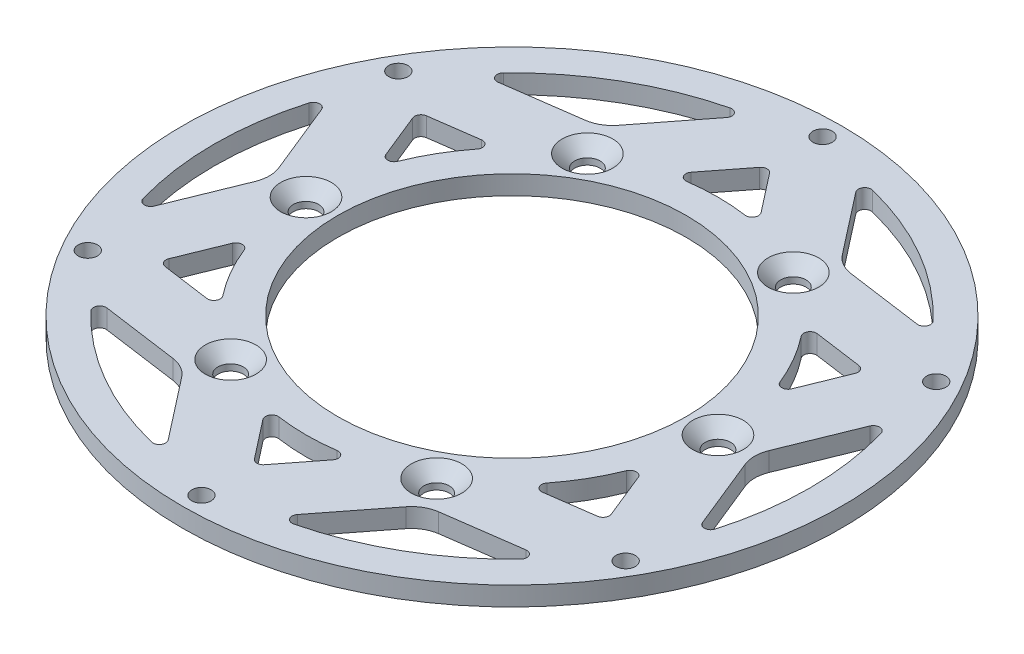
SolidWorks part; units mm, degrees
material "Thornel Mat VMA"
ref_plane "前视基准面" through (0, 0, 0) normal (0, 0, 1) x (1, 0, 0)
ref_plane "上视基准面" through (0, 0, 0) normal (0, 1, 0) x (1, 0, 0)
ref_plane "右视基准面" through (0, 0, 0) normal (1, 0, 0) x (0, 0, -1)
sketch "草图1" plane through (0, 0, 0) normal (0, 1, 0) x (1, 0, 0)
  circle A0 centre (0, 0) radius 52
  circle A1 centre (0, 0) radius 49 construction
  circle A2 centre (0, 0) radius 32.5 construction
  circle A3 centre (0, 49) radius 1.525
  circle A4 centre (-16.25, 28.1458) radius 2
  circle A5 centre (42.4352, 24.5) radius 1.525
  circle A6 centre (16.25, 28.1458) radius 2
  circle A7 centre (42.4352, -24.5) radius 1.525
  circle A8 centre (32.5, 0) radius 2
  circle A9 centre (0, -49) radius 1.525
  circle A10 centre (16.25, -28.1458) radius 2
  circle A11 centre (-42.4352, -24.5) radius 1.525
  circle A12 centre (-16.25, -28.1458) radius 2
  circle A13 centre (-42.4352, 24.5) radius 1.525
  circle A14 centre (-32.5, 0) radius 2
  circle A15 centre (0, 0) radius 27.5
  dimension "D1" = 104
  dimension "D2" = 65
  dimension "D3" = 3
  dimension "D4" = 3.05
  dimension "D5" = 4
  dimension "D7" = 55
  dimension "D6" = 6
extrude "凸台-拉伸1" add sketch "草图1" along normal blind 3
hole_wizard "孔1" positions "草图2" profile "草图3" legacy end condition through all
sketch "草图2" plane through (0, 3, 0) normal (0, 1, 0) x (1, 0, 0)
  point P0 (-16.25, 28.1458)
  point P7 (16.25, 28.1458)
  point P8 (32.5, 0)
  point P9 (16.25, -28.1458)
  point P10 (-16.25, -28.1458)
  point P11 (-32.5, 0)
  dimension "D1" = 6
sketch "草图3" plane through (-16.25, 3, -28.1458) normal (1, 0, 0) x (0, 0, 1)
  line L0 (0, 0) -> (0, 3)
  line L1 (0, 3) -> (2, 3)
  line L2 (2, 3) -> (2, 2)
  line L3 (2, 2) -> (4, 0)
  line L4 (4, 0) -> (0, 0)
  line L5 (0, -6.4453) -> (0, 115.525) construction
  line L6 (-2, 2) -> (-4, 0) construction
  dimension "直径" = 4
  dimension "深度" = 3
  dimension "锥坑角度" = 90
  dimension "锥坑直径" = 8
sketch "草图5" plane through (0, 3, 0) normal (0, 1, 0) x (1, 0, 0)
  line L0 (0, 49) -> (-16.25, 28.1458) construction
  line L1 (-16.25, 28.1458) -> (-42.4352, 24.5) construction
  line L2 (0, 49) -> (16.25, 28.1458) construction
  line L3 (-8.5013, 46.2248) -> (-18.9477, 32.8184)
  line L4 (-18.9477, 32.8184) -> (-35.7812, 30.4747)
  line L5 (0, 40.8653) -> (7.1365, 31.7068)
  line L6 (0, 40.8653) -> (-7.1365, 31.7068)
  line L11 (18.9477, 32.8184) -> (8.5013, 46.2248)
  line L12 (35.7812, 30.4747) -> (18.9477, 32.8184)
  line L13 (35.3904, 20.4326) -> (23.8906, 22.0338)
  line L14 (35.3904, 20.4326) -> (31.0271, 9.673)
  line L15 (37.8955, 0) -> (44.2824, 15.7501)
  line L16 (44.2824, -15.7501) -> (37.8955, 0)
  line L17 (35.3904, -20.4326) -> (31.0271, -9.673)
  line L18 (35.3904, -20.4326) -> (23.8906, -22.0338)
  line L19 (18.9477, -32.8184) -> (35.7812, -30.4747)
  line L20 (8.5013, -46.2248) -> (18.9477, -32.8184)
  line L21 (0, -40.8653) -> (7.1365, -31.7068)
  line L22 (0, -40.8653) -> (-7.1365, -31.7068)
  line L23 (-18.9477, -32.8184) -> (-8.5013, -46.2248)
  line L24 (-35.7812, -30.4747) -> (-18.9477, -32.8184)
  line L25 (-35.3904, -20.4326) -> (-23.8906, -22.0338)
  line L26 (-35.3904, -20.4326) -> (-31.0271, -9.673)
  line L27 (-37.8955, 0) -> (-44.2824, -15.7501)
  line L28 (-44.2824, 15.7501) -> (-37.8955, 0)
  line L29 (-35.3904, 20.4326) -> (-31.0271, 9.673)
  line L30 (-35.3904, 20.4326) -> (-23.8906, 22.0338)
  circle A0 centre (0, 0) radius 27.5 construction
  arc A1 (-8.5013, 46.2248) -> (-35.7812, 30.4747) centre (0, 0) ccw
  circle A2 centre (0, 0) radius 52 construction
  arc A3 (7.1365, 31.7068) -> (-7.1365, 31.7068) centre (0, 0) ccw
  arc A5 (35.7812, 30.4747) -> (8.5013, 46.2248) centre (0, 0) ccw
  arc A6 (31.0271, 9.673) -> (23.8906, 22.0338) centre (0, 0) ccw
  arc A7 (44.2824, -15.7501) -> (44.2824, 15.7501) centre (0, 0) ccw
  arc A8 (23.8906, -22.0338) -> (31.0271, -9.673) centre (0, 0) ccw
  arc A9 (8.5013, -46.2248) -> (35.7812, -30.4747) centre (0, 0) ccw
  arc A10 (-7.1365, -31.7068) -> (7.1365, -31.7068) centre (0, 0) ccw
  arc A11 (-35.7812, -30.4747) -> (-8.5013, -46.2248) centre (0, 0) ccw
  arc A12 (-31.0271, -9.673) -> (-23.8906, -22.0338) centre (0, 0) ccw
  arc A13 (-44.2824, 15.7501) -> (-44.2824, -15.7501) centre (0, 0) ccw
  arc A14 (-23.8906, 22.0338) -> (-31.0271, 9.673) centre (0, 0) ccw
  dimension "D3" = 5
  dimension "D5" = 5
  dimension "D6" = 5
  dimension "D1" = 5
  dimension "D2" = 5
  dimension "D7" = 5
  dimension "D4" = 6
extrude "切除-拉伸1" cut sketch "草图5" against normal blind 10
fillet "圆角1" radius 5 6 edges at (18.9477, 1.5, -32.8184) (37.8955, 1.5, 0) (18.9477, 1.5, 32.8184) (-18.9477, 1.5, 32.8184) (-37.8955, 1.5, 0) (-18.9477, 1.5, -32.8184)
fillet "圆角2" radius 1 30 edges at (-35.7812, 1.5, -30.4747) (-8.5013, 1.5, -46.2248) (-23.8906, 1.5, 22.0338) (-35.3904, 1.5, 20.4326) (-31.0271, 1.5, 9.673) (-44.2824, 1.5, 15.7501) (-44.2824, 1.5, -15.7501) (-31.0271, 1.5, -9.673) (-23.8906, 1.5, -22.0338) (7.1365, 1.5, -31.7068) (-7.1365, 1.5, -31.7068) (0, 1.5, -40.8653) (8.5013, 1.5, -46.2248) (35.7812, 1.5, -30.4747) (23.8906, 1.5, -22.0338) (35.3904, 1.5, -20.4326) (31.0271, 1.5, -9.673) (44.2824, 1.5, -15.7501) (44.2824, 1.5, 15.7501) (31.0271, 1.5, 9.673) (35.3904, 1.5, 20.4326) (23.8906, 1.5, 22.0338) (35.7812, 1.5, 30.4747) (8.5013, 1.5, 46.2248) (7.1365, 1.5, 31.7068) (0, 1.5, 40.8653) (-7.1365, 1.5, 31.7068) (-8.5013, 1.5, 46.2248) (-35.7812, 1.5, 30.4747) (-35.3904, 1.5, -20.4326)
